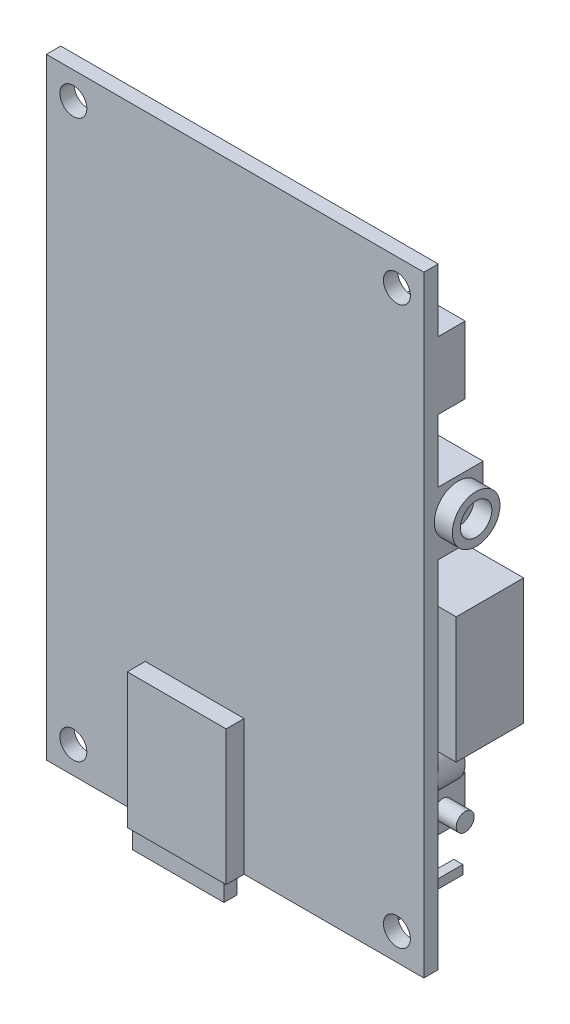
SolidWorks part; units mm, degrees
ref_plane "Piano frontale" through (0, 0, 0) normal (0, 0, 1) x (1, 0, 0)
ref_plane "Piano superiore" through (0, 0, 0) normal (0, 1, 0) x (1, 0, 0)
ref_plane "Piano destro" through (0, 0, 0) normal (1, 0, 0) x (0, 0, -1)
sketch "Schizzo1" plane through (0, 0, 0) normal (0, 0, 1) x (1, 0, 0)
  line L1 (-21, 34) -> (21, 34)
  line L2 (-21, 34) -> (-21, -34)
  line L3 (-21, -34) -> (21, -34)
  line L4 (21, 34) -> (21, -34)
  line L5 (-21, 34) -> (21, -34) construction
  line L6 (-21, -34) -> (21, 34) construction
  point P0 (0, 0)
  dimension "D1" = 42
  dimension "D2" = 68
extrude "Estrusione-Estrusione1" add sketch "Schizzo1" along normal blind 1.6
sketch "Schizzo2" plane through (0, 0, 0) normal (0, 0, -1) x (-1, 0, 0)
  line L0 (-21, 34) -> (21, 34) construction
  line L2 (-21, -34) -> (-21, 34) construction
  circle A0 centre (-18, 31) radius 1.5
  circle A1 centre (18, 31) radius 1.5
  circle A2 centre (18, -31) radius 1.5
  circle A3 centre (-18, -31) radius 1.5
  dimension "D1" = 3
  dimension "D2" = 3
  dimension "D3" = 2
  dimension "D4" = 2
extrude "Taglio-Estrusione1" cut sketch "Schizzo2" against normal up to next
sketch "Schizzo4" plane through (0, 0, 0) normal (0, 0, -1) x (-1, 0, 0)
  line L0 (-21, -34) -> (-21, 34) construction
  line L1 (-21, 27) -> (-15, 27)
  line L2 (-21, 27) -> (-21, 19.5)
  line L3 (-21, 19.5) -> (-15, 19.5)
  line L4 (-15, 27) -> (-15, 19.5)
  line L5 (-21, 34) -> (21, 34) construction
  dimension "D1" = 7
  dimension "D2" = 7.5
  dimension "D3" = 6
extrude "Estrusione-Estrusione2" add sketch "Schizzo4" along normal blind 3
sketch "Schizzo5" plane through (0, 0, 0) normal (0, 0, -1) x (-1, 0, 0)
  line L0 (-21, -34) -> (-21, 19.5) construction
  line L1 (-21, 12.5) -> (-9, 12.5)
  line L2 (-21, 12.5) -> (-21, 5.5)
  line L3 (-21, 5.5) -> (-9, 5.5)
  line L4 (-9, 12.5) -> (-9, 5.5)
  line L5 (-21, 19.5) -> (-15, 19.5) construction
  dimension "D1" = 12
  dimension "D2" = 7
  dimension "D3" = 7
extrude "Estrusione-Estrusione3" add sketch "Schizzo5" along normal blind 5
sketch "Schizzo6" plane through (21, 0, 0) normal (1, 0, 0) x (0, 0, -1)
  circle A0 centre (2.2146, 9.3191) radius 1.75
  circle A1 centre (2.2146, 9.3191) radius 2.65
  dimension "D1" = 0.9
extrude "Estrusione-Estrusione4" add sketch "Schizzo6" along normal blind 2
sketch "Schizzo7" plane through (0, 0, 0) normal (0, 0, -1) x (-1, 0, 0)
  line L0 (-21, -34) -> (-21, 5.5) construction
  line L1 (-21, 1) -> (-9, 1)
  line L2 (-21, 1) -> (-21, -13)
  line L3 (-21, -13) -> (-9, -13)
  line L4 (-9, 1) -> (-9, -13)
  line L5 (-21, 5.5) -> (-9, 5.5) construction
  dimension "D1" = 12
  dimension "D2" = 14
  dimension "D3" = 4.5
extrude "Estrusione-Estrusione5" add sketch "Schizzo7" along normal blind 7.5
sketch "Schizzo8" plane through (21, 0, 0) normal (1, 0, 0) x (0, 0, -1)
  line L1 (7.5, 1) -> (0, 1)
  line L2 (7.5, 1) -> (7.5, -13)
  line L3 (7.5, -13) -> (0, -13)
  line L4 (0, 1) -> (0, -13)
extrude "Estrusione-Estrusione6" add sketch "Schizzo8" along normal blind 2
sketch "Schizzo9" plane through (0, 0, 0) normal (0, 0, -1) x (-1, 0, 0)
  line L0 (-23, -13) -> (-9, -13) construction
  line L1 (-21, -34) -> (-21, -13) construction
  circle A0 centre (-18.5, -15.7) radius 2.5
  point P2 (-16, -13)
  dimension "D1" = 2.7
  dimension "D2" = 2.5
extrude "Estrusione-Estrusione7" add sketch "Schizzo9" along normal blind 3
sketch "Schizzo11" plane through (0, 0, 0) normal (0, 0, -1) x (-1, 0, 0)
  line L1 (-19, -18.5) -> (-16, -18.5)
  line L2 (-19, -18.5) -> (-19, -23)
  line L3 (-19, -23) -> (-16, -23)
  line L4 (-16, -18.5) -> (-16, -23)
  line L5 (21, -34) -> (-21, -34) construction
  line L6 (-21, -34) -> (-21, -15.7) construction
  dimension "D1" = 4.5
  dimension "D2" = 11
  dimension "D3" = 3
  dimension "D4" = 2
extrude "Estrusione-Estrusione8" add sketch "Schizzo11" along normal blind 5
sketch "Schizzo12" plane through (19, 0, 0) normal (1, 0, 0) x (0, 0, -1)
  line L0 (0, -18.5) -> (5, -23) construction
  circle A0 centre (2.5, -20.75) radius 1
extrude "Estrusione-Estrusione9" add sketch "Schizzo12" along normal blind 2.5
sketch "Schizzo13" plane through (0, 0, 1.6) normal (0, 0, 1) x (1, 0, 0)
  line L0 (-21, -34) -> (21, -34) construction
  line L1 (1, -34) -> (-10, -34)
  line L2 (1, -34) -> (1, -19)
  line L3 (1, -19) -> (-10, -19)
  line L4 (-10, -34) -> (-10, -19)
  line L5 (-21, 34) -> (-21, -34) construction
  dimension "D1" = 11
  dimension "D2" = 15
  dimension "D3" = 11
extrude "Estrusione-Estrusione10" add sketch "Schizzo13" along normal blind 2
sketch "Schizzo14" plane through (0, -34, 0) normal (0, -1, 0) x (1, 0, 0)
  line L1 (-9.5405, 3.4501) -> (0.6101, 3.4501)
  line L2 (-9.5405, 3.4501) -> (-9.5405, 2.009)
  line L3 (-9.5405, 2.009) -> (0.6101, 2.009)
  line L4 (0.6101, 3.4501) -> (0.6101, 2.009)
extrude "Estrusione-Estrusione11" add sketch "Schizzo14" along normal blind 2
sketch "Schizzo15" plane through (0, 0, 0) normal (0, 0, -1) x (-1, 0, 0)
  line L0 (18.3, 25.5) -> (18.3, 34) construction
  line L1 (15.8, 25.5) -> (20.8, 25.5)
  line L2 (15.8, 25.5) -> (15.8, -25.5)
  line L3 (15.8, -25.5) -> (20.8, -25.5)
  line L4 (20.8, 25.5) -> (20.8, -25.5)
  line L5 (-21, 34) -> (21, 34) construction
  line L6 (18.3, -25.5) -> (18.3, -34) construction
  line L7 (21, -34) -> (-21, -34) construction
  line L8 (21, 34) -> (21, -34) construction
  dimension "D1" = 5
  dimension "D2" = 51
  dimension "D3" = 0.2
extrude "Estrusione-Estrusione12" add sketch "Schizzo15" along normal blind 2
sketch "Schizzo16" plane through (0, 0, -2) normal (0, 0, -1) x (-1, 0, 0)
  line L0 (19.2027, 24.9081) -> (19.2027, 23.9081)
  line L1 (16.2027, 24.9081) -> (17.2027, 24.9081)
  line L2 (16.2027, 24.9081) -> (16.2027, 23.9081)
  line L3 (16.2027, 23.9081) -> (17.2027, 23.9081)
  line L4 (17.2027, 24.9081) -> (17.2027, 23.9081)
  line L5 (19.2027, 23.9081) -> (20.2027, 23.9081)
  line L6 (20.2027, 24.9081) -> (20.2027, 23.9081)
  line L7 (19.2027, 24.9081) -> (20.2027, 24.9081)
  line L8 (19.2027, 22.3481) -> (19.2027, 21.3481)
  line L9 (19.2027, 21.3481) -> (20.2027, 21.3481)
  line L10 (20.2027, 22.3481) -> (20.2027, 21.3481)
  line L11 (19.2027, 22.3481) -> (20.2027, 22.3481)
  line L12 (19.2027, 19.7881) -> (19.2027, 18.7881)
  line L13 (19.2027, 18.7881) -> (20.2027, 18.7881)
  line L14 (20.2027, 19.7881) -> (20.2027, 18.7881)
  line L15 (19.2027, 19.7881) -> (20.2027, 19.7881)
  line L16 (19.2027, 17.2281) -> (19.2027, 16.2281)
  line L17 (19.2027, 16.2281) -> (20.2027, 16.2281)
  line L18 (20.2027, 17.2281) -> (20.2027, 16.2281)
  line L19 (19.2027, 17.2281) -> (20.2027, 17.2281)
  line L20 (19.2027, 14.6681) -> (19.2027, 13.6681)
  line L21 (19.2027, 13.6681) -> (20.2027, 13.6681)
  line L22 (20.2027, 14.6681) -> (20.2027, 13.6681)
  line L23 (19.2027, 14.6681) -> (20.2027, 14.6681)
  line L24 (19.2027, 12.1081) -> (19.2027, 11.1081)
  line L25 (19.2027, 11.1081) -> (20.2027, 11.1081)
  line L26 (20.2027, 12.1081) -> (20.2027, 11.1081)
  line L27 (19.2027, 12.1081) -> (20.2027, 12.1081)
  line L28 (19.2027, 9.5481) -> (19.2027, 8.5481)
  line L29 (19.2027, 8.5481) -> (20.2027, 8.5481)
  line L30 (20.2027, 9.5481) -> (20.2027, 8.5481)
  line L31 (19.2027, 9.5481) -> (20.2027, 9.5481)
  line L32 (19.2027, 6.9881) -> (19.2027, 5.9881)
  line L33 (19.2027, 5.9881) -> (20.2027, 5.9881)
  line L34 (20.2027, 6.9881) -> (20.2027, 5.9881)
  line L35 (19.2027, 6.9881) -> (20.2027, 6.9881)
  line L36 (19.2027, 4.4281) -> (19.2027, 3.4281)
  line L37 (19.2027, 3.4281) -> (20.2027, 3.4281)
  line L38 (20.2027, 4.4281) -> (20.2027, 3.4281)
  line L39 (19.2027, 4.4281) -> (20.2027, 4.4281)
  line L40 (19.2027, 1.8681) -> (19.2027, 0.8681)
  line L41 (19.2027, 0.8681) -> (20.2027, 0.8681)
  line L42 (20.2027, 1.8681) -> (20.2027, 0.8681)
  line L43 (19.2027, 1.8681) -> (20.2027, 1.8681)
  line L44 (19.2027, -0.6919) -> (19.2027, -1.6919)
  line L45 (19.2027, -1.6919) -> (20.2027, -1.6919)
  line L46 (20.2027, -0.6919) -> (20.2027, -1.6919)
  line L47 (19.2027, -0.6919) -> (20.2027, -0.6919)
  line L48 (19.2027, -3.2519) -> (19.2027, -4.2519)
  line L49 (19.2027, -4.2519) -> (20.2027, -4.2519)
  line L50 (20.2027, -3.2519) -> (20.2027, -4.2519)
  line L51 (19.2027, -3.2519) -> (20.2027, -3.2519)
  line L52 (19.2027, -5.8119) -> (19.2027, -6.8119)
  line L53 (19.2027, -6.8119) -> (20.2027, -6.8119)
  line L54 (20.2027, -5.8119) -> (20.2027, -6.8119)
  line L55 (19.2027, -5.8119) -> (20.2027, -5.8119)
  line L56 (19.2027, -8.3719) -> (19.2027, -9.3719)
  line L57 (19.2027, -9.3719) -> (20.2027, -9.3719)
  line L58 (20.2027, -8.3719) -> (20.2027, -9.3719)
  line L59 (19.2027, -8.3719) -> (20.2027, -8.3719)
  line L60 (19.2027, -10.9319) -> (19.2027, -11.9319)
  line L61 (19.2027, -11.9319) -> (20.2027, -11.9319)
  line L62 (20.2027, -10.9319) -> (20.2027, -11.9319)
  line L63 (19.2027, -10.9319) -> (20.2027, -10.9319)
  line L64 (19.2027, -13.4919) -> (19.2027, -14.4919)
  line L65 (19.2027, -14.4919) -> (20.2027, -14.4919)
  line L66 (20.2027, -13.4919) -> (20.2027, -14.4919)
  line L67 (19.2027, -13.4919) -> (20.2027, -13.4919)
  line L68 (19.2027, -16.0519) -> (19.2027, -17.0519)
  line L69 (19.2027, -17.0519) -> (20.2027, -17.0519)
  line L70 (20.2027, -16.0519) -> (20.2027, -17.0519)
  line L71 (19.2027, -16.0519) -> (20.2027, -16.0519)
  line L72 (19.2027, -18.6119) -> (19.2027, -19.6119)
  line L73 (19.2027, -19.6119) -> (20.2027, -19.6119)
  line L74 (20.2027, -18.6119) -> (20.2027, -19.6119)
  line L75 (19.2027, -18.6119) -> (20.2027, -18.6119)
  line L76 (19.2027, -21.1719) -> (19.2027, -22.1719)
  line L77 (19.2027, -22.1719) -> (20.2027, -22.1719)
  line L78 (20.2027, -21.1719) -> (20.2027, -22.1719)
  line L79 (19.2027, -21.1719) -> (20.2027, -21.1719)
  line L80 (19.2027, -23.7319) -> (19.2027, -24.7319)
  line L81 (19.2027, -24.7319) -> (20.2027, -24.7319)
  line L82 (20.2027, -23.7319) -> (20.2027, -24.7319)
  line L83 (19.2027, -23.7319) -> (20.2027, -23.7319)
  line L84 (16.2027, 22.3481) -> (16.2027, 21.3481)
  line L85 (16.2027, 21.3481) -> (17.2027, 21.3481)
  line L86 (17.2027, 22.3481) -> (17.2027, 21.3481)
  line L87 (16.2027, 22.3481) -> (17.2027, 22.3481)
  line L88 (16.2027, 19.7881) -> (16.2027, 18.7881)
  line L89 (16.2027, 18.7881) -> (17.2027, 18.7881)
  line L90 (17.2027, 19.7881) -> (17.2027, 18.7881)
  line L91 (16.2027, 19.7881) -> (17.2027, 19.7881)
  line L92 (16.2027, 17.2281) -> (16.2027, 16.2281)
  line L93 (16.2027, 16.2281) -> (17.2027, 16.2281)
  line L94 (17.2027, 17.2281) -> (17.2027, 16.2281)
  line L95 (16.2027, 17.2281) -> (17.2027, 17.2281)
  line L96 (16.2027, 14.6681) -> (16.2027, 13.6681)
  line L97 (16.2027, 13.6681) -> (17.2027, 13.6681)
  line L98 (17.2027, 14.6681) -> (17.2027, 13.6681)
  line L99 (16.2027, 14.6681) -> (17.2027, 14.6681)
  line L100 (16.2027, 12.1081) -> (16.2027, 11.1081)
  line L101 (16.2027, 11.1081) -> (17.2027, 11.1081)
  line L102 (17.2027, 12.1081) -> (17.2027, 11.1081)
  line L103 (16.2027, 12.1081) -> (17.2027, 12.1081)
  line L104 (16.2027, 9.5481) -> (16.2027, 8.5481)
  line L105 (16.2027, 8.5481) -> (17.2027, 8.5481)
  line L106 (17.2027, 9.5481) -> (17.2027, 8.5481)
  line L107 (16.2027, 9.5481) -> (17.2027, 9.5481)
  line L108 (16.2027, 6.9881) -> (16.2027, 5.9881)
  line L109 (16.2027, 5.9881) -> (17.2027, 5.9881)
  line L110 (17.2027, 6.9881) -> (17.2027, 5.9881)
  line L111 (16.2027, 6.9881) -> (17.2027, 6.9881)
  line L112 (16.2027, 4.4281) -> (16.2027, 3.4281)
  line L113 (16.2027, 3.4281) -> (17.2027, 3.4281)
  line L114 (17.2027, 4.4281) -> (17.2027, 3.4281)
  line L115 (16.2027, 4.4281) -> (17.2027, 4.4281)
  line L116 (16.2027, 1.8681) -> (16.2027, 0.8681)
  line L117 (16.2027, 0.8681) -> (17.2027, 0.8681)
  line L118 (17.2027, 1.8681) -> (17.2027, 0.8681)
  line L119 (16.2027, 1.8681) -> (17.2027, 1.8681)
  line L120 (16.2027, -0.6919) -> (16.2027, -1.6919)
  line L121 (16.2027, -1.6919) -> (17.2027, -1.6919)
  line L122 (17.2027, -0.6919) -> (17.2027, -1.6919)
  line L123 (16.2027, -0.6919) -> (17.2027, -0.6919)
  line L124 (16.2027, -3.2519) -> (16.2027, -4.2519)
  line L125 (16.2027, -4.2519) -> (17.2027, -4.2519)
  line L126 (17.2027, -3.2519) -> (17.2027, -4.2519)
  line L127 (16.2027, -3.2519) -> (17.2027, -3.2519)
  line L128 (16.2027, -5.8119) -> (16.2027, -6.8119)
  line L129 (16.2027, -6.8119) -> (17.2027, -6.8119)
  line L130 (17.2027, -5.8119) -> (17.2027, -6.8119)
  line L131 (16.2027, -5.8119) -> (17.2027, -5.8119)
  line L132 (16.2027, -8.3719) -> (16.2027, -9.3719)
  line L133 (16.2027, -9.3719) -> (17.2027, -9.3719)
  line L134 (17.2027, -8.3719) -> (17.2027, -9.3719)
  line L135 (16.2027, -8.3719) -> (17.2027, -8.3719)
  line L136 (16.2027, -10.9319) -> (16.2027, -11.9319)
  line L137 (16.2027, -11.9319) -> (17.2027, -11.9319)
  line L138 (17.2027, -10.9319) -> (17.2027, -11.9319)
  line L139 (16.2027, -10.9319) -> (17.2027, -10.9319)
  line L140 (16.2027, -13.4919) -> (16.2027, -14.4919)
  line L141 (16.2027, -14.4919) -> (17.2027, -14.4919)
  line L142 (17.2027, -13.4919) -> (17.2027, -14.4919)
  line L143 (16.2027, -13.4919) -> (17.2027, -13.4919)
  line L144 (16.2027, -16.0519) -> (16.2027, -17.0519)
  line L145 (16.2027, -17.0519) -> (17.2027, -17.0519)
  line L146 (17.2027, -16.0519) -> (17.2027, -17.0519)
  line L147 (16.2027, -16.0519) -> (17.2027, -16.0519)
  line L148 (16.2027, -18.6119) -> (16.2027, -19.6119)
  line L149 (16.2027, -19.6119) -> (17.2027, -19.6119)
  line L150 (17.2027, -18.6119) -> (17.2027, -19.6119)
  line L151 (16.2027, -18.6119) -> (17.2027, -18.6119)
  line L152 (16.2027, -21.1719) -> (16.2027, -22.1719)
  line L153 (16.2027, -22.1719) -> (17.2027, -22.1719)
  line L154 (17.2027, -21.1719) -> (17.2027, -22.1719)
  line L155 (16.2027, -21.1719) -> (17.2027, -21.1719)
  line L156 (16.2027, -23.7319) -> (16.2027, -24.7319)
  line L157 (16.2027, -24.7319) -> (17.2027, -24.7319)
  line L158 (17.2027, -23.7319) -> (17.2027, -24.7319)
  line L159 (16.2027, -23.7319) -> (17.2027, -23.7319)
  dimension "D1" = 1
  dimension "D2" = 2
  dimension "D3" = 20
extrude "Estrusione-Estrusione13" add sketch "Schizzo16" along normal blind 7
sketch "Schizzo17" plane through (0, 0, 0) normal (0, 0, -1) x (-1, 0, 0)
  line L0 (-9, -6) -> (-7, -6) construction
  line L1 (-9, -13) -> (-9, 1) construction
  line L3 (-8, -2.5) -> (-6, -2.5)
  line L4 (-8, -2.5) -> (-8, -9.5)
  line L5 (-8, -9.5) -> (-6, -9.5)
  line L6 (-6, -2.5) -> (-6, -9.5)
  line L7 (-8, -2.5) -> (-6, -9.5) construction
  line L8 (-8, -9.5) -> (-6, -2.5) construction
  dimension "D1" = 7
  dimension "D2" = 2
  dimension "D3" = 2
extrude "Estrusione-Estrusione14" add sketch "Schizzo17" along normal blind 2
sketch "Schizzo18" plane through (0, 0, -2) normal (0, 0, -1) x (-1, 0, 0)
  line L0 (-7, -2.5) -> (-7, -9.5) construction
  line L1 (-6, -2.5) -> (-8, -2.5) construction
  line L2 (-8, -9.5) -> (-6, -9.5) construction
  line L3 (-7.5, -5.5) -> (-6.5, -5.5)
  line L4 (-7.5, -2.8383) -> (-6.5, -2.8383)
  line L5 (-7.5, -2.8383) -> (-7.5, -3.8383)
  line L6 (-7.5, -3.8383) -> (-6.5, -3.8383)
  line L7 (-6.5, -2.8383) -> (-6.5, -3.8383)
  line L8 (-7.5, -2.8383) -> (-6.5, -3.8383) construction
  line L9 (-7.5, -3.8383) -> (-6.5, -2.8383) construction
  line L10 (-7.5, -5.5) -> (-7.5, -6.5)
  line L11 (-7.5, -6.5) -> (-6.5, -6.5)
  line L12 (-6.5, -5.5) -> (-6.5, -6.5)
  line L13 (-7.5, -5.5) -> (-6.5, -6.5) construction
  line L14 (-7.5, -6.5) -> (-6.5, -5.5) construction
  line L15 (-7.5, -8.1617) -> (-6.5, -8.1617)
  line L16 (-7.5, -8.1617) -> (-7.5, -9.1617)
  line L17 (-7.5, -9.1617) -> (-6.5, -9.1617)
  line L18 (-6.5, -8.1617) -> (-6.5, -9.1617)
  line L19 (-7.5, -8.1617) -> (-6.5, -9.1617) construction
  line L20 (-7.5, -9.1617) -> (-6.5, -8.1617) construction
  line L21 (-7.3169, -2.8383) -> (-7.3169, -2.5) construction
  line L22 (-6, -2.5) -> (-8, -2.5) construction
  line L23 (-7.3169, -9.1617) -> (-7.3169, -9.5) construction
  point P6 (-7, -3.3383)
  point P11 (-7, -6)
  point P17 (-7, -8.6617)
  dimension "D1" = 1
  dimension "D2" = 3
extrude "Estrusione-Estrusione15" add sketch "Schizzo18" along normal blind 7
sketch "Schizzo19" plane through (0, 0, 0) normal (0, 0, -1) x (-1, 0, 0)
  line L0 (-21, -34) -> (-21, -15.7) construction
  line L1 (-15, -31) -> (-8, -31)
  line L2 (-15, -31) -> (-15, -33)
  line L3 (-15, -33) -> (-8, -33)
  line L4 (-8, -31) -> (-8, -33)
  line L5 (-15, -31) -> (-8, -33) construction
  line L6 (-15, -33) -> (-8, -31) construction
  line L7 (21, -34) -> (-21, -34) construction
  point P0 (-11.5, -32)
  dimension "D1" = 6
  dimension "D2" = 1
  dimension "D3" = 7
  dimension "D4" = 2
extrude "Estrusione-Estrusione16" add sketch "Schizzo19" along normal blind 2
sketch "Schizzo20" plane through (0, 0, -2) normal (0, 0, -1) x (-1, 0, 0)
  line L0 (-15, -32) -> (-8, -32) construction
  line L1 (-15, -31) -> (-15, -33) construction
  line L2 (-8, -33) -> (-8, -31) construction
  line L3 (-12, -31.5) -> (-11, -31.5)
  line L4 (-14.7269, -31.5) -> (-13.7269, -31.5)
  line L5 (-14.7269, -31.5) -> (-14.7269, -32.5)
  line L6 (-14.7269, -32.5) -> (-13.7269, -32.5)
  line L7 (-13.7269, -31.5) -> (-13.7269, -32.5)
  line L8 (-14.7269, -31.5) -> (-13.7269, -32.5) construction
  line L9 (-14.7269, -32.5) -> (-13.7269, -31.5) construction
  line L10 (-12, -31.5) -> (-12, -32.5)
  line L11 (-12, -32.5) -> (-11, -32.5)
  line L12 (-11, -31.5) -> (-11, -32.5)
  line L13 (-12, -31.5) -> (-11, -32.5) construction
  line L14 (-12, -32.5) -> (-11, -31.5) construction
  line L15 (-9.2731, -31.5) -> (-8.2731, -31.5)
  line L16 (-9.2731, -31.5) -> (-9.2731, -32.5)
  line L17 (-9.2731, -32.5) -> (-8.2731, -32.5)
  line L18 (-8.2731, -31.5) -> (-8.2731, -32.5)
  line L19 (-9.2731, -31.5) -> (-8.2731, -32.5) construction
  line L20 (-9.2731, -32.5) -> (-8.2731, -31.5) construction
  line L21 (-14.7269, -31.7255) -> (-15, -31.7255) construction
  line L22 (-8.2731, -31.7255) -> (-8, -31.7255) construction
  point P6 (-14.2269, -32)
  point P12 (-11.5, -32)
  point P17 (-8.7731, -32)
  dimension "D1" = 1
  dimension "D2" = 1
  dimension "D3" = 3
extrude "Estrusione-Estrusione17" add sketch "Schizzo20" along normal blind 7
